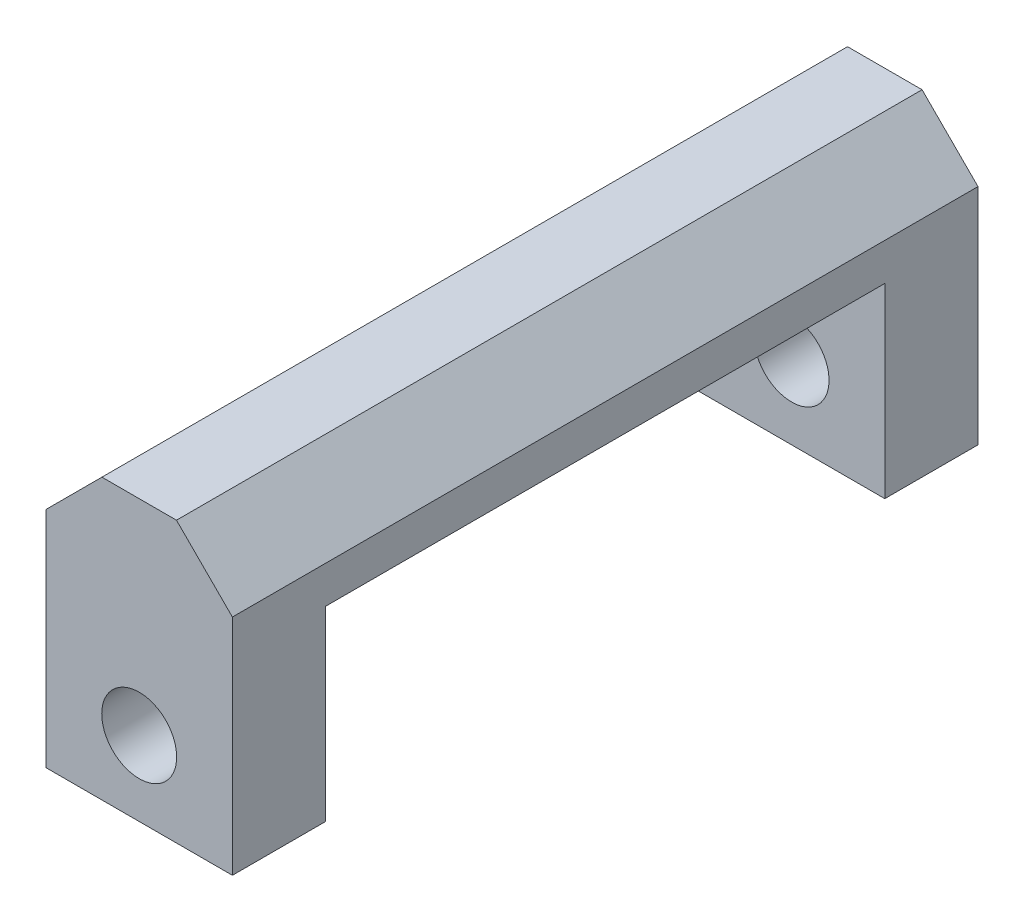
SolidWorks part; units mm, degrees
ref_plane "Front Plane" through (0, 0, 0) normal (0, 0, 1) x (1, 0, 0)
ref_plane "Top Plane" through (0, 0, 0) normal (0, 1, 0) x (1, 0, 0)
ref_plane "Right Plane" through (0, 0, 0) normal (1, 0, 0) x (0, 0, -1)
sketch "Sketch1" plane through (0, 0, 0) normal (1, 0, 0) x (0, 0, -1)
  line L0 (25.4, 0) -> (-25.4, 0)
  line L1 (-25.4, 0) -> (-25.4, -19.05)
  line L2 (-25.4, -19.05) -> (-19.05, -19.05)
  line L3 (-19.05, -19.05) -> (-19.05, -6.35)
  line L4 (-19.05, -6.35) -> (19.05, -6.35)
  line L5 (0, -6.35) -> (0, 49993.65) construction
  line L6 (19.05, -19.05) -> (19.05, -6.35)
  line L7 (25.4, -19.05) -> (19.05, -19.05)
  line L8 (25.4, 0) -> (25.4, -19.05)
  point P11 (0, -6.35)
  point P12 (0, 0)
  dimension "D1" = 6.35
  dimension "D2" = 6.35
  dimension "D3" = 12.7
  dimension "D4" = 19.05
extrude "Boss-Extrude1" add sketch "Sketch1" along normal blind 12.7
hole_wizard "Tap Drill for 1/4-20 Tap1" positions "3DSketch2" profile "Sketch4" hole size "1/4-20" standard "ANSI Inch" end condition through all
sketch3d "3DSketch2"
  line L0 (12.7, -19.05, -25.4) -> (12.7, 0, -25.4) construction
  line L1 (12.7, -19.05, -25.4) -> (0, -19.05, -25.4) construction
  point P0 (6.35, -13.97, -25.4)
  dimension "D1" = 6.35
  dimension "D2" = 5.08
sketch "Sketch4" plane through (6.35, -13.97, -25.4) normal (1, 0, 0) x (0, 1, 0)
  line L0 (0, 0) -> (0, 50.8)
  line L1 (0, 50.8) -> (2.5527, 50.8)
  line L2 (2.5527, 50.8) -> (2.5527, 0)
  line L5 (2.5527, 0) -> (0, 0)
  line L11 (0, -6.35) -> (0, 107.95) construction
  dimension "Thru Hole Dia." = 5.1054
  dimension "Thru Hole Depth" = 50.8
chamfer "Chamfer1" distance 3.81 angle 45 2 edges at (0, 0, 0) (12.7, 0, 0)
